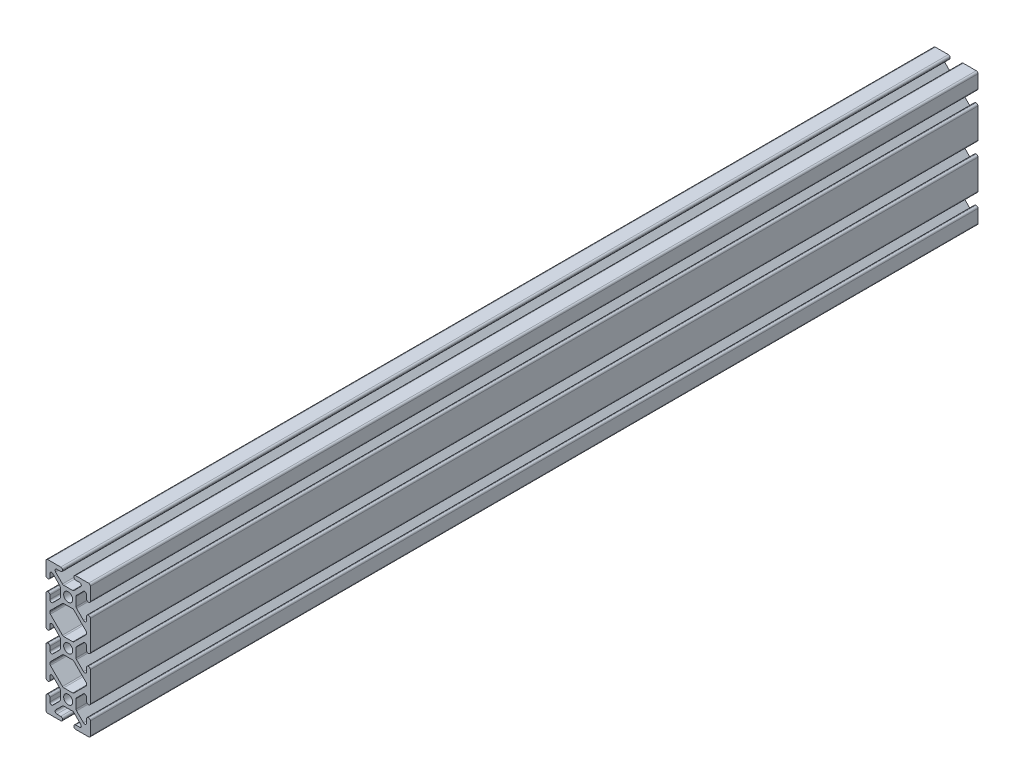
SolidWorks part; units mm, degrees
ref_plane "Front Plane" through (0, 0, 0) normal (0, 0, 1) x (1, 0, 0)
ref_plane "Top Plane" through (0, 0, 0) normal (0, 1, 0) x (1, 0, 0)
ref_plane "Right Plane" through (0, 0, 0) normal (1, 0, 0) x (0, 0, -1)
sketch "Sketch1" plane through (0, 0, 0) normal (0, 0, 1) x (1, 0, 0)
  line L0 (-12.7, 38.1) -> (-12.7, 12.7) construction
  line L1 (-12.7, -38.1) -> (12.7, -38.1) construction
  line L2 (-12.7, 12.7) -> (-12.7, -12.7) construction
  line L3 (-12.7, 38.1) -> (12.7, 38.1) construction
  line L4 (-12.7, -12.7) -> (-12.7, -38.1) construction
  line L5 (-12.7, -38.1) -> (12.7, 38.1) construction
  line L6 (-12.7, 38.1) -> (12.7, -38.1) construction
  line L7 (12.7, 38.1) -> (12.7, 12.7) construction
  line L8 (12.7, 12.7) -> (12.7, -12.7) construction
  line L9 (12.7, -12.7) -> (12.7, -38.1) construction
  line L10 (-12.7, 12.7) -> (12.7, 12.7) construction
  line L11 (-12.7, -12.7) -> (12.7, -12.7) construction
  line L12 (12.7, -12.7) -> (-12.7, -38.1) construction
  line L13 (12.7, -38.1) -> (-12.7, -12.7) construction
  line L14 (0, 38.1) -> (0, -38.1) construction
  line L15 (12.7, 12.7) -> (-12.7, 38.1) construction
  line L16 (12.7, 38.1) -> (-12.7, 12.7) construction
  line L17 (-12.7, 37.084) -> (-12.7, 29.6672)
  line L18 (-11.684, 28.6512) -> (-11.5062, 28.6512)
  line L19 (-10.4902, 29.6672) -> (-10.4902, 31.8748)
  line L20 (-8.7558, 32.5932) -> (-4.8188, 28.6562)
  line L21 (-4.5212, 27.9378) -> (-4.5212, 22.8622)
  line L22 (-4.8188, 22.1438) -> (-8.7558, 18.2068)
  line L23 (-10.4902, 18.9252) -> (-10.4902, 21.1328)
  line L24 (-11.5062, 22.1488) -> (-11.684, 22.1488)
  line L25 (-12.7, 21.1328) -> (-12.7, 4.2672)
  line L26 (-12.7, 0) -> (12.7, 0) construction
  line L27 (-12.7, -25.4) -> (12.7, -25.4) construction
  line L28 (-12.7, 25.4) -> (12.7, 25.4) construction
  line L29 (4.2672, 38.1) -> (11.684, 38.1)
  line L30 (3.2512, 36.9062) -> (3.2512, 37.084)
  line L31 (6.4748, 35.8902) -> (4.2672, 35.8902)
  line L32 (3.2562, 30.2188) -> (7.1932, 34.1558)
  line L33 (-2.5378, 29.9212) -> (2.5378, 29.9212)
  line L34 (-7.1932, 34.1558) -> (-3.2562, 30.2188)
  line L35 (-4.2672, 35.8902) -> (-6.4748, 35.8902)
  line L36 (-3.2512, 37.084) -> (-3.2512, 36.9062)
  line L37 (-11.684, 38.1) -> (-4.2672, 38.1)
  line L38 (4.5212, 2.5378) -> (4.5212, -2.5378)
  line L39 (11.5062, 22.1488) -> (11.684, 22.1488)
  line L40 (10.4902, 18.9252) -> (10.4902, 21.1328)
  line L41 (4.8188, 22.1438) -> (8.7558, 18.2068)
  line L42 (4.5212, 27.9378) -> (4.5212, 22.8622)
  line L43 (8.7558, 32.5932) -> (4.8188, 28.6562)
  line L44 (10.4902, 29.6672) -> (10.4902, 31.8748)
  line L45 (11.684, 28.6512) -> (11.5062, 28.6512)
  line L46 (12.7, 37.084) -> (12.7, 29.6672)
  line L47 (-10.4902, 12.4736) -> (-10.4902, 12.9264)
  line L48 (-10.1926, 13.6448) -> (-3.2562, 20.5812)
  line L49 (-2.5378, 20.8788) -> (2.5378, 20.8788)
  line L50 (10.4902, 12.4736) -> (10.4902, 12.9264)
  line L51 (10.1926, 13.6448) -> (3.2562, 20.5812)
  line L52 (10.1926, 11.7552) -> (3.2562, 4.8188)
  line L53 (-2.5378, 4.5212) -> (2.5378, 4.5212)
  line L54 (-10.1926, 11.7552) -> (-3.2562, 4.8188)
  line L55 (-2.5378, -4.5212) -> (2.5378, -4.5212)
  line L56 (-10.1926, -11.7552) -> (-3.2562, -4.8188)
  line L57 (10.1926, -11.7552) -> (3.2562, -4.8188)
  line L58 (10.4902, -12.4736) -> (10.4902, -12.9264)
  line L59 (10.1926, -13.6448) -> (3.2562, -20.5812)
  line L60 (-2.5378, -20.8788) -> (2.5378, -20.8788)
  line L61 (-10.1926, -13.6448) -> (-3.2562, -20.5812)
  line L62 (-10.4902, -12.4736) -> (-10.4902, -12.9264)
  line L63 (4.8188, -3.2562) -> (8.7558, -7.1932)
  line L64 (11.5062, -22.1488) -> (11.684, -22.1488)
  line L65 (10.4902, -18.9252) -> (10.4902, -21.1328)
  line L66 (4.8188, -22.1438) -> (8.7558, -18.2068)
  line L67 (4.5212, -27.9378) -> (4.5212, -22.8622)
  line L68 (8.7558, -32.5932) -> (4.8188, -28.6562)
  line L69 (10.4902, -29.6672) -> (10.4902, -31.8748)
  line L70 (11.684, -28.6512) -> (11.5062, -28.6512)
  line L71 (12.7, -37.084) -> (12.7, -29.6672)
  line L72 (3.2512, -36.9062) -> (3.2512, -37.084)
  line L73 (6.4748, -35.8902) -> (4.2672, -35.8902)
  line L74 (3.2562, -30.2188) -> (7.1932, -34.1558)
  line L75 (-2.5378, -29.9212) -> (2.5378, -29.9212)
  line L76 (-7.1932, -34.1558) -> (-3.2562, -30.2188)
  line L77 (-4.2672, -35.8902) -> (-6.4748, -35.8902)
  line L78 (-3.2512, -37.084) -> (-3.2512, -36.9062)
  line L79 (-11.684, -38.1) -> (-4.2672, -38.1)
  line L80 (4.2672, -38.1) -> (11.684, -38.1)
  line L81 (4.8188, 3.2562) -> (8.7558, 7.1932)
  line L82 (-11.5062, -22.1488) -> (-11.684, -22.1488)
  line L83 (-10.4902, -18.9252) -> (-10.4902, -21.1328)
  line L84 (-4.8188, -22.1438) -> (-8.7558, -18.2068)
  line L85 (-4.5212, -27.9378) -> (-4.5212, -22.8622)
  line L86 (-8.7558, -32.5932) -> (-4.8188, -28.6562)
  line L87 (-10.4902, -29.6672) -> (-10.4902, -31.8748)
  line L88 (-11.684, -28.6512) -> (-11.5062, -28.6512)
  line L89 (-12.7, -37.084) -> (-12.7, -29.6672)
  line L90 (-4.8188, 3.2562) -> (-8.7558, 7.1932)
  line L91 (-10.4902, 6.4748) -> (-10.4902, 4.2672)
  line L92 (-11.5062, 3.2512) -> (-11.684, 3.2512)
  line L93 (-4.5212, 2.5378) -> (-4.5212, -2.5378)
  line L94 (-12.7, -21.1328) -> (-12.7, -4.2672)
  line L95 (-4.8188, -3.2562) -> (-8.7558, -7.1932)
  line L96 (-10.4902, -6.4748) -> (-10.4902, -4.2672)
  line L97 (-11.5062, -3.2512) -> (-11.684, -3.2512)
  line L98 (10.4902, -6.4748) -> (10.4902, -4.2672)
  line L99 (10.4902, 6.4748) -> (10.4902, 4.2672)
  line L100 (11.5062, 3.2512) -> (11.684, 3.2512)
  line L101 (11.5062, -3.2512) -> (11.684, -3.2512)
  line L102 (12.7, -21.1328) -> (12.7, -4.2672)
  line L103 (12.7, 21.1328) -> (12.7, 4.2672)
  circle A0 centre (0, 25.4) radius 2.6035
  circle A1 centre (0, 0) radius 2.6035
  circle A2 centre (0, -25.4) radius 2.6035
  arc A3 (-12.7, 21.1328) -> (-11.684, 22.1488) centre (-11.684, 21.1328) cw
  arc A4 (-11.5062, 22.1488) -> (-10.4902, 21.1328) centre (-11.5062, 21.1328) cw
  arc A5 (-10.4902, 18.9252) -> (-8.7558, 18.2068) centre (-9.4742, 18.9252) ccw
  arc A6 (-4.8188, 22.1438) -> (-4.5212, 22.8622) centre (-5.5372, 22.8622) ccw
  arc A7 (-4.5212, 27.9378) -> (-4.8188, 28.6562) centre (-5.5372, 27.9378) ccw
  arc A8 (-8.7558, 32.5932) -> (-10.4902, 31.8748) centre (-9.4742, 31.8748) ccw
  arc A9 (-10.4902, 29.6672) -> (-11.5062, 28.6512) centre (-11.5062, 29.6672) cw
  arc A10 (-11.684, 28.6512) -> (-12.7, 29.6672) centre (-11.684, 29.6672) cw
  arc A11 (4.2672, 38.1) -> (3.2512, 37.084) centre (4.2672, 37.084) ccw
  arc A12 (3.2512, 36.9062) -> (4.2672, 35.8902) centre (4.2672, 36.9062) ccw
  arc A13 (6.4748, 35.8902) -> (7.1932, 34.1558) centre (6.4748, 34.8742) cw
  arc A14 (3.2562, 30.2188) -> (2.5378, 29.9212) centre (2.5378, 30.9372) cw
  arc A15 (-2.5378, 29.9212) -> (-3.2562, 30.2188) centre (-2.5378, 30.9372) cw
  arc A16 (-7.1932, 34.1558) -> (-6.4748, 35.8902) centre (-6.4748, 34.8742) cw
  arc A17 (-4.2672, 35.8902) -> (-3.2512, 36.9062) centre (-4.2672, 36.9062) ccw
  arc A18 (-3.2512, 37.084) -> (-4.2672, 38.1) centre (-4.2672, 37.084) ccw
  arc A19 (12.7, 21.1328) -> (11.684, 22.1488) centre (11.684, 21.1328) ccw
  arc A20 (11.5062, 22.1488) -> (10.4902, 21.1328) centre (11.5062, 21.1328) ccw
  arc A21 (10.4902, 18.9252) -> (8.7558, 18.2068) centre (9.4742, 18.9252) cw
  arc A22 (4.8188, 22.1438) -> (4.5212, 22.8622) centre (5.5372, 22.8622) cw
  arc A23 (4.5212, 27.9378) -> (4.8188, 28.6562) centre (5.5372, 27.9378) cw
  arc A24 (8.7558, 32.5932) -> (10.4902, 31.8748) centre (9.4742, 31.8748) cw
  arc A25 (10.4902, 29.6672) -> (11.5062, 28.6512) centre (11.5062, 29.6672) ccw
  arc A26 (11.684, 28.6512) -> (12.7, 29.6672) centre (11.684, 29.6672) ccw
  arc A27 (12.7, 37.084) -> (11.684, 38.1) centre (11.684, 37.084) ccw
  arc A28 (-11.684, 38.1) -> (-12.7, 37.084) centre (-11.684, 37.084) ccw
  arc A29 (-10.1926, 13.6448) -> (-10.4902, 12.9264) centre (-9.4742, 12.9264) ccw
  arc A30 (-2.5378, 20.8788) -> (-3.2562, 20.5812) centre (-2.5378, 19.8628) ccw
  arc A31 (10.1926, 13.6448) -> (10.4902, 12.9264) centre (9.4742, 12.9264) cw
  arc A32 (2.5378, 20.8788) -> (3.2562, 20.5812) centre (2.5378, 19.8628) cw
  arc A33 (10.1926, 11.7552) -> (10.4902, 12.4736) centre (9.4742, 12.4736) ccw
  arc A34 (2.5378, 4.5212) -> (3.2562, 4.8188) centre (2.5378, 5.5372) ccw
  arc A35 (-2.5378, 4.5212) -> (-3.2562, 4.8188) centre (-2.5378, 5.5372) cw
  arc A36 (-10.1926, 11.7552) -> (-10.4902, 12.4736) centre (-9.4742, 12.4736) cw
  arc A37 (2.5378, -4.5212) -> (3.2562, -4.8188) centre (2.5378, -5.5372) cw
  arc A38 (-2.5378, -4.5212) -> (-3.2562, -4.8188) centre (-2.5378, -5.5372) ccw
  arc A39 (10.1926, -11.7552) -> (10.4902, -12.4736) centre (9.4742, -12.4736) cw
  arc A40 (10.1926, -13.6448) -> (10.4902, -12.9264) centre (9.4742, -12.9264) ccw
  arc A41 (2.5378, -20.8788) -> (3.2562, -20.5812) centre (2.5378, -19.8628) ccw
  arc A42 (-2.5378, -20.8788) -> (-3.2562, -20.5812) centre (-2.5378, -19.8628) cw
  arc A43 (-10.1926, -13.6448) -> (-10.4902, -12.9264) centre (-9.4742, -12.9264) cw
  arc A44 (-10.1926, -11.7552) -> (-10.4902, -12.4736) centre (-9.4742, -12.4736) ccw
  arc A45 (12.7, -21.1328) -> (11.684, -22.1488) centre (11.684, -21.1328) cw
  arc A46 (11.5062, -22.1488) -> (10.4902, -21.1328) centre (11.5062, -21.1328) cw
  arc A47 (10.4902, -18.9252) -> (8.7558, -18.2068) centre (9.4742, -18.9252) ccw
  arc A48 (4.8188, -22.1438) -> (4.5212, -22.8622) centre (5.5372, -22.8622) ccw
  arc A49 (4.5212, -27.9378) -> (4.8188, -28.6562) centre (5.5372, -27.9378) ccw
  arc A50 (8.7558, -32.5932) -> (10.4902, -31.8748) centre (9.4742, -31.8748) ccw
  arc A51 (10.4902, -29.6672) -> (11.5062, -28.6512) centre (11.5062, -29.6672) cw
  arc A52 (11.684, -28.6512) -> (12.7, -29.6672) centre (11.684, -29.6672) cw
  arc A53 (4.2672, -38.1) -> (3.2512, -37.084) centre (4.2672, -37.084) cw
  arc A54 (3.2512, -36.9062) -> (4.2672, -35.8902) centre (4.2672, -36.9062) cw
  arc A55 (6.4748, -35.8902) -> (7.1932, -34.1558) centre (6.4748, -34.8742) ccw
  arc A56 (3.2562, -30.2188) -> (2.5378, -29.9212) centre (2.5378, -30.9372) ccw
  arc A57 (-2.5378, -29.9212) -> (-3.2562, -30.2188) centre (-2.5378, -30.9372) ccw
  arc A58 (-7.1932, -34.1558) -> (-6.4748, -35.8902) centre (-6.4748, -34.8742) ccw
  arc A59 (-4.2672, -35.8902) -> (-3.2512, -36.9062) centre (-4.2672, -36.9062) cw
  arc A60 (-3.2512, -37.084) -> (-4.2672, -38.1) centre (-4.2672, -37.084) cw
  arc A61 (12.7, -37.084) -> (11.684, -38.1) centre (11.684, -37.084) cw
  arc A62 (-12.7, -21.1328) -> (-11.684, -22.1488) centre (-11.684, -21.1328) ccw
  arc A63 (-11.5062, -22.1488) -> (-10.4902, -21.1328) centre (-11.5062, -21.1328) ccw
  arc A64 (-10.4902, -18.9252) -> (-8.7558, -18.2068) centre (-9.4742, -18.9252) cw
  arc A65 (-4.8188, -22.1438) -> (-4.5212, -22.8622) centre (-5.5372, -22.8622) cw
  arc A66 (-4.5212, -27.9378) -> (-4.8188, -28.6562) centre (-5.5372, -27.9378) cw
  arc A67 (-8.7558, -32.5932) -> (-10.4902, -31.8748) centre (-9.4742, -31.8748) cw
  arc A68 (-10.4902, -29.6672) -> (-11.5062, -28.6512) centre (-11.5062, -29.6672) ccw
  arc A69 (-11.684, -28.6512) -> (-12.7, -29.6672) centre (-11.684, -29.6672) ccw
  arc A70 (-11.684, -38.1) -> (-12.7, -37.084) centre (-11.684, -37.084) cw
  arc A71 (-4.8188, 3.2562) -> (-4.5212, 2.5378) centre (-5.5372, 2.5378) cw
  arc A72 (-10.4902, 6.4748) -> (-8.7558, 7.1932) centre (-9.4742, 6.4748) cw
  arc A73 (-11.5062, 3.2512) -> (-10.4902, 4.2672) centre (-11.5062, 4.2672) ccw
  arc A74 (-12.7, 4.2672) -> (-11.684, 3.2512) centre (-11.684, 4.2672) ccw
  arc A75 (-4.8188, -3.2562) -> (-4.5212, -2.5378) centre (-5.5372, -2.5378) ccw
  arc A76 (-10.4902, -6.4748) -> (-8.7558, -7.1932) centre (-9.4742, -6.4748) ccw
  arc A77 (-11.5062, -3.2512) -> (-10.4902, -4.2672) centre (-11.5062, -4.2672) cw
  arc A78 (-12.7, -4.2672) -> (-11.684, -3.2512) centre (-11.684, -4.2672) cw
  arc A79 (4.8188, 3.2562) -> (4.5212, 2.5378) centre (5.5372, 2.5378) ccw
  arc A80 (4.8188, -3.2562) -> (4.5212, -2.5378) centre (5.5372, -2.5378) cw
  arc A81 (10.4902, 6.4748) -> (8.7558, 7.1932) centre (9.4742, 6.4748) ccw
  arc A82 (10.4902, -6.4748) -> (8.7558, -7.1932) centre (9.4742, -6.4748) cw
  arc A83 (11.5062, -3.2512) -> (10.4902, -4.2672) centre (11.5062, -4.2672) ccw
  arc A84 (11.5062, 3.2512) -> (10.4902, 4.2672) centre (11.5062, 4.2672) cw
  arc A85 (12.7, -4.2672) -> (11.684, -3.2512) centre (11.684, -4.2672) ccw
  arc A86 (12.7, 4.2672) -> (11.684, 3.2512) centre (11.684, 4.2672) cw
  point P0 (0, 0)
  point P26 (-12.7, 22.1488)
  point P41 (-12.7, 28.6512)
  point P107 (-6.7244, 17.113)
  point P120 (0, 20.8788)
  point P121 (10.4902, 12.7)
  point P132 (-10.4902, 12.7)
  point P249 (-4.5212, 0)
  dimension "D2" = 5.207
  dimension "D8" = 1.016
  dimension "D9" = 3.2512
  dimension "D10" = 1.1049
  dimension "D1" = 25.4
  dimension "D3" = 2.2098
  dimension "D4" = 6.5024
  dimension "D5" = 4.5212
  dimension "D6" = 1.1049
  dimension "D7" = 1.1049
  dimension "D11" = 4.5212
extrude "Main Extrusion" add sketch "Sketch1" along normal mid plane 508
sketch "Sketch2" plane through (0, 0, 254) normal (0, 0, 1) x (1, 0, 0)
  line L0 (-4.2672, 38.1) -> (-11.684, 38.1) construction
  line L1 (-12.7, -38.1) -> (12.7, -38.1) construction
  line L2 (-12.7, 38.1) -> (-12.7, 12.7) construction
  line L3 (-12.7, 38.1) -> (12.7, 38.1) construction
  line L4 (-12.7, 21.1328) -> (-12.7, 4.2672) construction
  line L5 (-12.7, -38.1) -> (12.7, 38.1) construction
  line L6 (-12.7, 38.1) -> (12.7, -38.1) construction
  line L7 (-12.7, 12.7) -> (-12.7, -12.7) construction
  line L8 (0, 38.1) -> (0, -38.1) construction
  line L9 (-12.7, -4.2672) -> (-12.7, -21.1328) construction
  line L10 (-12.7, -12.7) -> (-12.7, -38.1) construction
  line L11 (12.7, 38.1) -> (12.7, 12.7) construction
  line L12 (12.7, 4.2672) -> (12.7, 21.1328) construction
  line L13 (12.7, 12.7) -> (12.7, -12.7) construction
  line L14 (12.7, -21.1328) -> (12.7, -4.2672) construction
  line L15 (12.7, -12.7) -> (12.7, -38.1) construction
  line L16 (-12.7, 25.4) -> (12.7, 25.4) construction
  line L17 (-12.7, 0) -> (12.7, 0) construction
  line L18 (-12.7, -25.4) -> (12.7, -25.4) construction
  line L19 (-12.7, 12.7) -> (12.7, 12.7) construction
  line L20 (-12.7, -12.7) -> (12.7, -12.7) construction
  line L21 (-3.2512, 36.9062) -> (-3.2512, 37.084) construction
  line L22 (-10.4902, 38.1) -> (-9.4742, 38.1)
  line L23 (-6.477, 38.1) -> (-5.461, 38.1)
  line L24 (-12.7, 38.1) -> (12.7, 12.7) construction
  line L25 (12.7, 12.7) -> (-12.7, -12.7) construction
  line L26 (-12.7, -12.7) -> (12.7, -38.1) construction
  line L27 (-12.7, -38.1) -> (12.7, -12.7) construction
  line L28 (12.7, -12.7) -> (-12.7, 12.7) construction
  line L29 (-12.7, 12.7) -> (12.7, 38.1) construction
  line L30 (6.477, 38.1) -> (5.461, 38.1)
  line L31 (10.4902, 38.1) -> (9.4742, 38.1)
  line L32 (-12.7, 14.9098) -> (-12.7, 15.9258)
  line L33 (-12.7, 18.923) -> (-12.7, 19.939)
  line L34 (-12.7, 31.877) -> (-12.7, 30.861)
  line L35 (-12.7, 35.8902) -> (-12.7, 34.8742)
  line L36 (12.7, 35.8902) -> (12.7, 34.8742)
  line L37 (12.7, 31.877) -> (12.7, 30.861)
  line L38 (12.7, 18.923) -> (12.7, 19.939)
  line L39 (12.7, 14.9098) -> (12.7, 15.9258)
  line L40 (12.7, 10.4902) -> (12.7, 9.4742)
  line L41 (12.7, 6.477) -> (12.7, 5.461)
  line L42 (-12.7, 10.4902) -> (-12.7, 9.4742)
  line L43 (-12.7, 6.477) -> (-12.7, 5.461)
  line L44 (12.7, -6.477) -> (12.7, -5.461)
  line L45 (12.7, -10.4902) -> (12.7, -9.4742)
  line L46 (12.7, -14.9098) -> (12.7, -15.9258)
  line L47 (12.7, -18.923) -> (12.7, -19.939)
  line L48 (12.7, -31.877) -> (12.7, -30.861)
  line L49 (12.7, -35.8902) -> (12.7, -34.8742)
  line L50 (10.4902, -38.1) -> (9.4742, -38.1)
  line L51 (6.477, -38.1) -> (5.461, -38.1)
  line L52 (-6.477, -38.1) -> (-5.461, -38.1)
  line L53 (-10.4902, -38.1) -> (-9.4742, -38.1)
  line L54 (-12.7, -35.8902) -> (-12.7, -34.8742)
  line L55 (-12.7, -31.877) -> (-12.7, -30.861)
  line L56 (-12.7, -18.923) -> (-12.7, -19.939)
  line L57 (-12.7, -14.9098) -> (-12.7, -15.9258)
  line L58 (-12.7, -10.4902) -> (-12.7, -9.4742)
  line L59 (-12.7, -6.477) -> (-12.7, -5.461)
  arc A0 (-10.4902, 38.1) -> (-9.4742, 38.1) centre (-9.9822, 38.1) ccw
  arc A1 (-6.477, 38.1) -> (-5.461, 38.1) centre (-5.969, 38.1) ccw
  arc A2 (6.477, 38.1) -> (5.461, 38.1) centre (5.969, 38.1) cw
  arc A3 (10.4902, 38.1) -> (9.4742, 38.1) centre (9.9822, 38.1) cw
  arc A4 (-12.7, 14.9098) -> (-12.7, 15.9258) centre (-12.7, 15.4178) ccw
  arc A5 (-12.7, 18.923) -> (-12.7, 19.939) centre (-12.7, 19.431) ccw
  arc A6 (-12.7, 31.877) -> (-12.7, 30.861) centre (-12.7, 31.369) cw
  arc A7 (-12.7, 35.8902) -> (-12.7, 34.8742) centre (-12.7, 35.3822) cw
  arc A8 (12.7, 35.8902) -> (12.7, 34.8742) centre (12.7, 35.3822) ccw
  arc A9 (12.7, 31.877) -> (12.7, 30.861) centre (12.7, 31.369) ccw
  arc A10 (12.7, 18.923) -> (12.7, 19.939) centre (12.7, 19.431) cw
  arc A11 (12.7, 14.9098) -> (12.7, 15.9258) centre (12.7, 15.4178) cw
  arc A12 (12.7, 10.4902) -> (12.7, 9.4742) centre (12.7, 9.9822) ccw
  arc A13 (12.7, 6.477) -> (12.7, 5.461) centre (12.7, 5.969) ccw
  arc A14 (-12.7, 10.4902) -> (-12.7, 9.4742) centre (-12.7, 9.9822) cw
  arc A15 (-12.7, 6.477) -> (-12.7, 5.461) centre (-12.7, 5.969) cw
  arc A16 (12.7, -6.477) -> (12.7, -5.461) centre (12.7, -5.969) cw
  arc A17 (12.7, -10.4902) -> (12.7, -9.4742) centre (12.7, -9.9822) cw
  arc A18 (12.7, -14.9098) -> (12.7, -15.9258) centre (12.7, -15.4178) ccw
  arc A19 (12.7, -18.923) -> (12.7, -19.939) centre (12.7, -19.431) ccw
  arc A20 (12.7, -31.877) -> (12.7, -30.861) centre (12.7, -31.369) cw
  arc A21 (12.7, -35.8902) -> (12.7, -34.8742) centre (12.7, -35.3822) cw
  arc A22 (10.4902, -38.1) -> (9.4742, -38.1) centre (9.9822, -38.1) ccw
  arc A23 (6.477, -38.1) -> (5.461, -38.1) centre (5.969, -38.1) ccw
  arc A24 (-6.477, -38.1) -> (-5.461, -38.1) centre (-5.969, -38.1) cw
  arc A25 (-10.4902, -38.1) -> (-9.4742, -38.1) centre (-9.9822, -38.1) cw
  arc A26 (-12.7, -35.8902) -> (-12.7, -34.8742) centre (-12.7, -35.3822) ccw
  arc A27 (-12.7, -31.877) -> (-12.7, -30.861) centre (-12.7, -31.369) ccw
  arc A28 (-12.7, -18.923) -> (-12.7, -19.939) centre (-12.7, -19.431) cw
  arc A29 (-12.7, -14.9098) -> (-12.7, -15.9258) centre (-12.7, -15.4178) cw
  arc A30 (-12.7, -10.4902) -> (-12.7, -9.4742) centre (-12.7, -9.9822) ccw
  arc A31 (-12.7, -6.477) -> (-12.7, -5.461) centre (-12.7, -5.969) ccw
  point P0 (0, 0)
  dimension "D1" = 0.508
  dimension "D2" = 2.2098
  dimension "D3" = 2.2098
